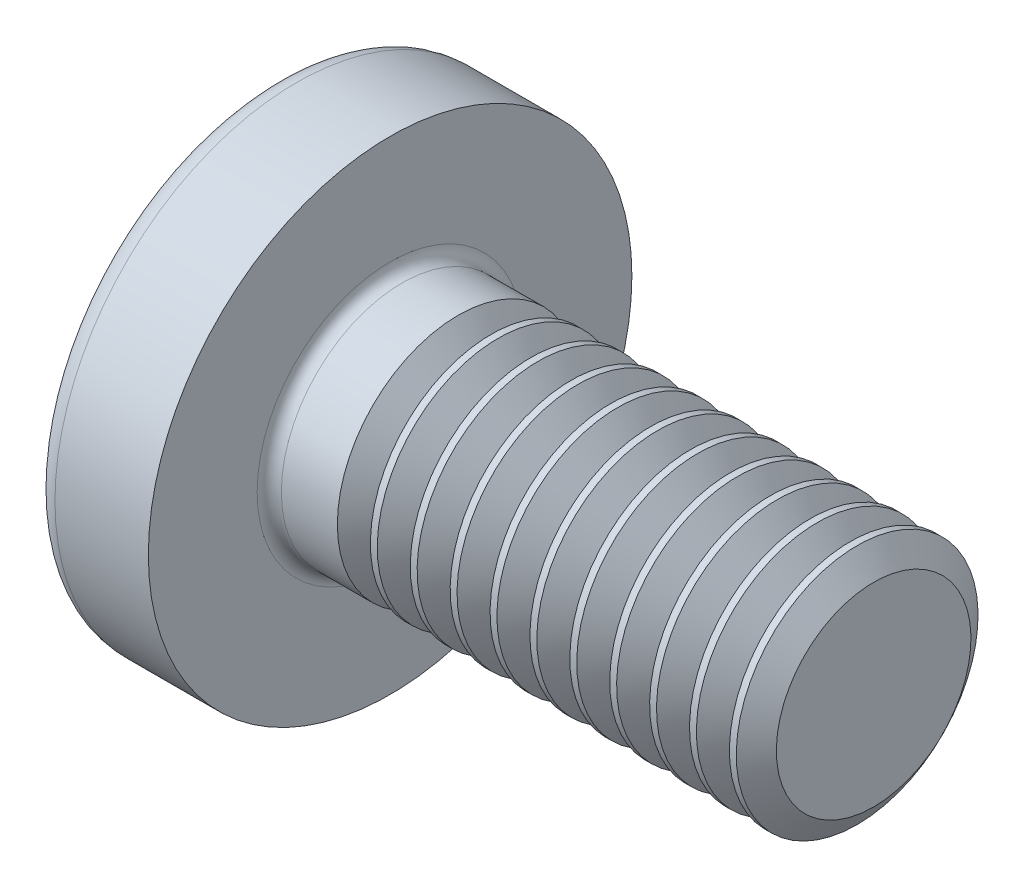
SolidWorks part; units mm, degrees
ref_plane "Plane1" through (0, 0, 0) normal (0, 0, 1) x (1, 0, 0)
ref_plane "Plane2" through (0, 0, 0) normal (0, 1, 0) x (1, 0, 0)
ref_plane "Plane3" through (0, 0, 0) normal (1, 0, 0) x (0, 0, -1)
sketch "BodySke" plane through (0, 0, 0) normal (0, 0, 1) x (1, 0, 0)
  line L0 (3.1, 2) -> (3.1, 4)
  line L1 (3.45, 6.35) -> (3.45, -3.175) construction
  line L2 (-25.4, 0) -> (127, 0) construction
  line L3 (11.1, 0) -> (0, 0)
  line L4 (3.1, 2) -> (11.1, 2)
  line L5 (11.1, 2) -> (11.1, 0)
  line L6 (1.5553, 4) -> (3.1, 4)
  line L8 (3.1, 6.35) -> (3.1, -3.175) construction
  arc A0 (1.2654, 3.8534) -> (0, 0) centre (6.5, 0) ccw
  arc A2 (1.2654, 3.8534) -> (1.5553, 4) centre (1.5553, 3.64) cw
  dimension "Head_crown_rad" = 6.5
  dimension "Head_fillet_rad" = 0.36
  dimension "Length" = 8
  dimension "Head_ht" = 3.1
  dimension "Head_dia" = 8
  dimension "Advance" = 0.7
  dimension "Thread_nom" = 8
  dimension "Diameter" = 4
revolve "Base-Revolve" add sketch "BodySke"
cosmetic thread "ThreadCosmetic" [suppressed]
fillet "Fillet1" radius 0.2 1 edges at (3.1, 0, 2)
sketch "Sketch3" plane through (0, 0, 0) normal (1, 0, 0) x (0, 0, -1)
  line L0 (0.515, -2.15) -> (-0.515, -2.15)
  line L1 (0.515, -2.15) -> (0.515, 2.15)
  line L2 (-0.515, 2.15) -> (0.515, 2.15)
  line L3 (-0.515, 2.15) -> (-0.515, -2.15)
  dimension "Cross_dia" = 4.3
  dimension "D1" = 2.15
  dimension "Cross_width" = 1.03
  dimension "D2" = 0.515
ref_plane "Plane4" through (2.34, 0, 0) normal (1, 0, 0) x (0, 0, -1)
sketch "Sketch4" plane through (2.34, 0, 0) normal (1, 0, 0) x (0, 0, -1)
  line L0 (0.515, -0.9833) -> (-0.515, -0.9833)
  line L1 (0.515, -0.9833) -> (0.515, 0.9833)
  line L2 (-0.515, 0.9833) -> (0.515, 0.9833)
  line L3 (-0.515, 0.9833) -> (-0.515, -0.9833)
  dimension "D1" = 1.03
  dimension "D2" = 1.9666
  dimension "D3" = 0.515
  dimension "D4" = 0.9833
loft "Recess" cut profiles "Sketch3", "Sketch4"
pattern_circular "RecPat" count 2 every 90 about axis through (0, 0, 0) along (1, 0, 0) of "Recess"
sketch "RecCorSke" plane through (0, 0, 0) normal (0, 0, 1) x (1, 0, 0)
  line L0 (-3.175, 0) -> (15.875, 0) construction
  line L1 (-25.4, 0) -> (127, 0) construction
  line L2 (0, 0) -> (0, 1.0146)
  line L3 (0, 1.0146) -> (2.34, 0.851)
  line L4 (2.34, 0.851) -> (2.6165, 0)
  line L5 (2.6165, 0) -> (0, 0)
  dimension "Diameter" = 1.702
  dimension "Depth" = 2.34
  dimension "Draft_angle" = 4
  dimension "Bottom_angle" = 18
revolve "RecessCore" cut sketch "RecCorSke" angle 360 about L0
sketch "ThdSchSke" plane through (0, 0, 0) normal (0, 0, 1) x (1, 0, 0)
  line L0 (4.5, -1.61) -> (4.2269, -2)
  line L1 (4.5, -1.61) -> (4.7731, -2)
  line L2 (4.7731, -2) -> (4.7731, -2.5)
  line L3 (-3.175, 0) -> (5.1513, 0) construction
  line L5 (4.7731, -2.5) -> (4.2269, -2.5)
  line L6 (4.2269, -2.5) -> (4.2269, -2)
  dimension "Diameter" = 4
  dimension "SideAngle" = 55
  dimension "VeeAngle" = 70
  dimension "Thread_minor" = 3.22
  dimension "Overcut" = 5
  dimension "Start" = 4.5
revolve "ThreadSchematic" cut sketch "ThdSchSke" angle 360 about L3
pattern_linear "ThdSchPat" count 11 spacing 0.66 along (1, 0, 0) of "ThreadSchematic"
equation "\"D1@Sketch3\" = \"Cross_dia@Sketch3\" / 2"
equation "\"D2@Sketch3\" = \"Cross_width@Sketch3\" / 2"
equation "\"Depth@RecCorSke\" = \"Cross_depth@Plane4\""
equation "\"D1@Sketch4\" = \"Cross_width@Sketch3\""
equation "\"D2@Sketch4\" = \"Cross_dia@Sketch3\" - 2.0 * \"Cross_depth@Plane4\" * tan(26.5  * 0.017453292)"
equation "\"D3@Sketch4\" = \"D1@Sketch4\" / 2"
equation "\"D4@Sketch4\" = \"D2@Sketch4\" / 2"
equation "\"Thread_length@ThreadCosmetic\" = ((sgn( (\"Length@BodySke\" - \"Advance@BodySke\" * 2.0 ) - \"Thread_nom@BodySke\" )-1)*( (\"Length@BodySke\" - \"Advance@BodySke\" * 2.0 ) - \"Thread_nom@BodySke\" ))/-2+ \"Thread_nom@BodySke\""
equation "\"Thread_minor@ThdSchSke\" = \"Thread_minor@ThreadCosmetic\""
equation "\"Diameter@ThdSchSke\" = \"Diameter@BodySke\""
equation "\"Overcut@ThdSchSke\" = \"Diameter@BodySke\" * 1.25"
equation "\"Start@ThdSchSke\" = \"Head_ht@BodySke\" + \"Length@BodySke\" - \"Thread_length@ThreadCosmetic\"  '---Non-countersunk---"
equation "\"Num_threads@ThdSchPat\" = int( \"Thread_length@ThreadCosmetic\" / \"Advance@BodySke\" + 0.999 )  + 1"
equation "\"Advance@ThdSchPat\" = \"Thread_length@ThreadCosmetic\" /  (\"Num_threads@ThdSchPat\" - 1) 'relax it"
